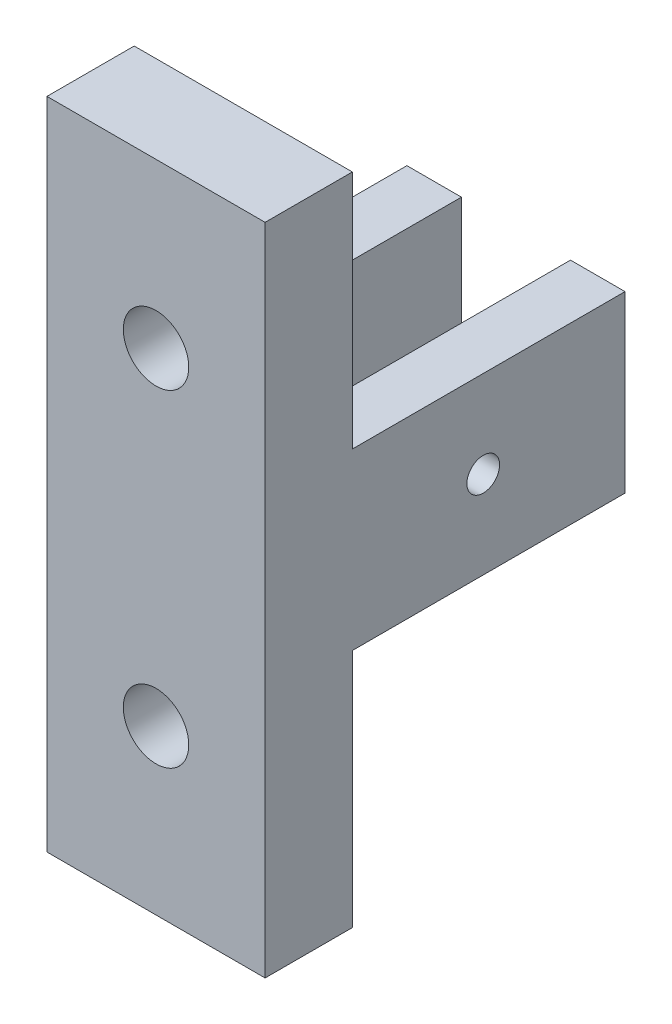
SolidWorks part; units mm, degrees
ref_plane "前视基准面" through (0, 0, 0) normal (0, 0, 1) x (1, 0, 0)
ref_plane "上视基准面" through (0, 0, 0) normal (0, 1, 0) x (1, 0, 0)
ref_plane "右视基准面" through (0, 0, 0) normal (1, 0, 0) x (0, 0, -1)
sketch "草图1" plane through (0, 0, 0) normal (0, 0, 1) x (1, 0, 0)
  line L1 (-10, -30) -> (10, -30)
  line L2 (-10, -30) -> (-10, 30)
  line L3 (-10, 30) -> (10, 30)
  line L4 (10, -30) -> (10, 30)
  line L5 (-10, -30) -> (10, 30) construction
  line L6 (-10, 30) -> (10, -30) construction
  circle A0 centre (0, 15) radius 3
  circle A1 centre (0, -15) radius 3
  point P0 (0, 0)
  dimension "D3" = 6
  dimension "D4" = 6
  dimension "D5" = 15
  dimension "D6" = 30
  dimension "D7" = 10
  dimension "D8" = 10
  dimension "D1" = 60
  dimension "D2" = 20
extrude "凸台-拉伸1" add sketch "草图1" along normal blind 8
sketch "草图3" plane through (0, 0, 0) normal (0, 0, -1) x (-1, 0, 0)
  line L0 (10, 30) -> (10, -30) construction
  line L1 (-5, -6) -> (-5, -8)
  line L2 (-10, -8) -> (-10, 8)
  line L3 (-10, 8) -> (-5, 8)
  line L4 (10, -8) -> (10, 8)
  line L5 (-10, -8) -> (10, 8) construction
  line L6 (-10, 8) -> (10, -8) construction
  line L7 (-5, 8) -> (-5, 6)
  line L8 (-5, -8) -> (-10, -8)
  line L9 (-5, -6) -> (-5, 6)
  line L10 (5, -6) -> (5, -8)
  line L11 (5, -6) -> (5, 6)
  line L12 (-5, -6) -> (5, 6) construction
  line L13 (-5, 6) -> (5, -6) construction
  line L14 (5, 6) -> (5, 8)
  line L15 (5, 8) -> (10, 8)
  line L16 (5, -8) -> (10, -8)
  point P0 (0, 0)
  point P8 (0, 0)
  dimension "D1" = 16
  dimension "D2" = 10
  dimension "D3" = 12
extrude "凸台-拉伸3" add sketch "草图3" along normal blind 25
sketch "草图4" plane through (10, 0, 0) normal (1, 0, 0) x (0, 0, -1)
  circle A0 centre (12, 0) radius 1.5
  dimension "D1" = 3
  dimension "D2" = 12
extrude "切除-拉伸1" cut sketch "草图4" against normal blind 25
